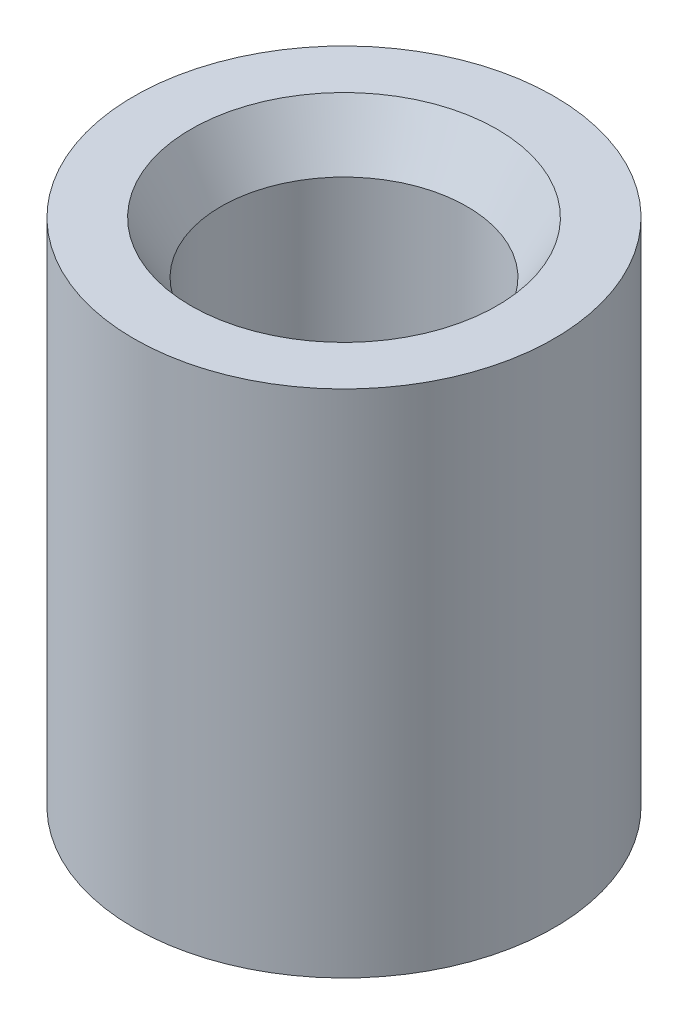
SolidWorks part; units mm, degrees
ref_plane "Спереди" through (0, 0, 0) normal (0, 0, 1) x (1, 0, 0)
ref_plane "Сверху" through (0, 0, 0) normal (0, 1, 0) x (1, 0, 0)
ref_plane "Справа" through (0, 0, 0) normal (1, 0, 0) x (0, 0, -1)
sketch "Эскиз1" plane through (0, 0, 0) normal (0, 1, 0) x (1, 0, 0)
  circle A0 centre (0, 0) radius 4.1
  circle A1 centre (0, 0) radius 7
  dimension "D1" = 8.2
  dimension "D2" = 14
extrude "Бобышка-Вытянуть1" add sketch "Эскиз1" along normal blind 17
sketch "Эскиз2" plane through (0, 0, 0) normal (0, -1, 0) x (1, 0, 0)
  circle A0 centre (0, 0) radius 7
extrude "Бобышка-Вытянуть2" add sketch "Эскиз2" against normal offset from surface (10 mm away) 7 up to face at (0, 17, 7)
chamfer "Фаска1" distance 1 angle 60 1 edges at (0, 17, 4.1)
